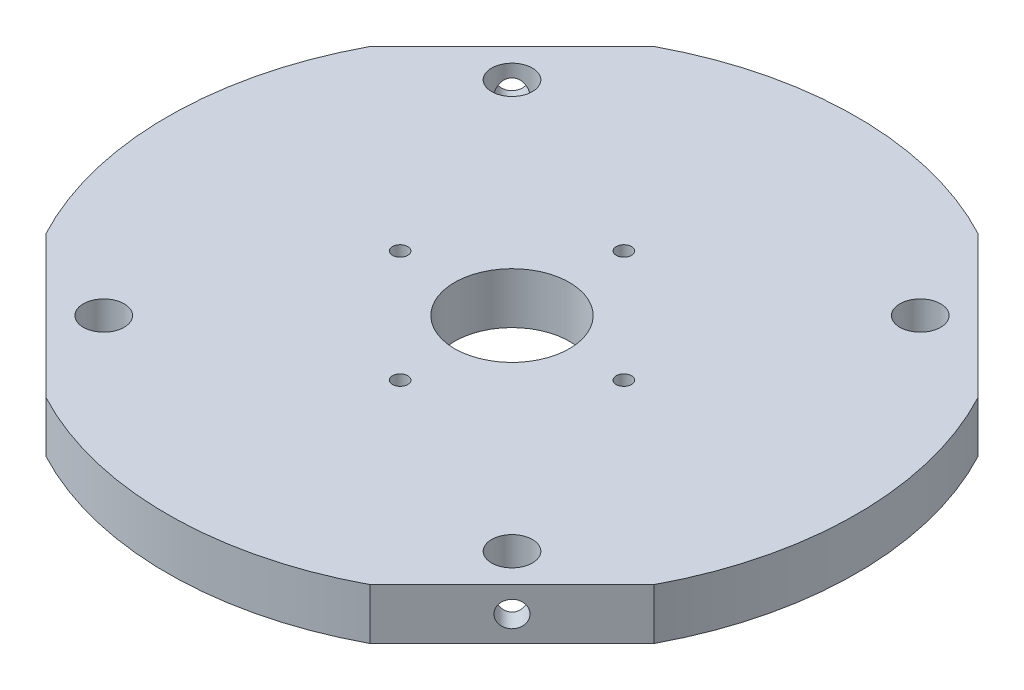
SolidWorks part; units mm, degrees
ref_plane "Front Plane" through (0, 0, 0) normal (0, 0, 1) x (1, 0, 0)
ref_plane "Top Plane" through (0, 0, 0) normal (0, 1, 0) x (1, 0, 0)
ref_plane "Right Plane" through (0, 0, 0) normal (1, 0, 0) x (0, 0, -1)
sketch "Sketch1" plane through (0, 0, 0) normal (0, 1, 0) x (1, 0, 0)
  circle A0 centre (0, 0) radius 67.5
  dimension "D1" = 135
extrude "Boss-Extrude1" add sketch "Sketch1" along normal blind 10
sketch "Sketch4" plane through (0, 10, 0) normal (0, 1, 0) x (1, 0, 0)
  line L0 (0, 67.5) -> (0, -67.5) construction
  line L1 (-67.5, 0) -> (67.5, 0) construction
  circle A0 centre (0, 0) radius 67.5 construction
  circle A1 centre (-40, 40) radius 4
  circle A2 centre (40, 40) radius 4
  circle A3 centre (40, -40) radius 4
  circle A4 centre (-40, -40) radius 4
  point P7 (0, 0)
  point P12 (0, 0)
  dimension "D3" = 8
  dimension "D1" = 40
  dimension "D2" = 40
extrude "Cut-Extrude1" cut sketch "Sketch4" against normal through all and the other way through all
sketch "Sketch5" plane through (0, 10, 0) normal (0, 1, 0) x (1, 0, 0)
  line L0 (-44.5962, 41.0607) -> (-41.0607, 44.5962) construction
  line L1 (-42.8284, 42.8284) -> (0, 0) construction
  line L2 (0, 67.5) -> (0, -67.5) construction
  line L3 (-31.7437, 59.57) -> (-59.57, 31.7437)
  line L4 (59.57, 31.7437) -> (31.7437, 59.57)
  line L5 (31.7437, -59.57) -> (59.57, -31.7437)
  line L6 (-59.57, -31.7437) -> (-31.7437, -59.57)
  line L7 (0, 0) -> (-45.6569, -45.6569) construction
  circle A0 centre (0, 0) radius 67.5 construction
  circle A1 centre (-40, 40) radius 4 construction
  point P5 (-42.8284, 42.8284)
  point P14 (0, 0)
  point P15 (-45.6569, 45.6569)
  dimension "D1" = 5
  dimension "D2" = 45
  dimension "D3" = 4
  dimension "D4" = 4
extrude "Cut-Extrude-Thin1" cut sketch "Sketch5" against normal through all thin
hole_wizard "Ø5.0mm Dowel Hole1" positions "Sketch6" profile "Sketch7" hole size "Ø5.0" standard "ANSI Metric"
sketch "Sketch6" plane through (45.6569, 0, 45.6569) normal (0.7071, 0, 0.7071) x (0.7071, 0, -0.7071)
  line L0 (0, 0) -> (0, 10) construction
  line L1 (-19.6762, 0) -> (19.6762, 0) construction
  line L2 (-19.6762, 10) -> (19.6762, 10) construction
  point P0 (0, 5)
sketch "Sketch7" plane through (45.6569, 5, 45.6569) normal (0, 1, 0) x (0.7071, 0, -0.7071)
  line L0 (0, 0) -> (0, 4)
  line L1 (0, 4) -> (2.5, 4)
  line L2 (2.5, 4) -> (2.5, 0)
  line L5 (2.5, 0) -> (0, 0)
  line L11 (0, -6.35) -> (0, 107.95) construction
  dimension "Thru Hole Dia." = 5
  dimension "Thru Hole Depth" = 4
pattern_circular "CirPattern1" count 4 over 360 about axis through (0, 10, 0) along (0, -1, 0) of "Ø5.0mm Dowel Hole1"
hole_wizard "Ø3.0mm Dowel Hole1" positions "Sketch8" profile "Sketch9" hole size "Ø3.0" standard "DIN" end condition through all
sketch "Sketch8" plane through (0, 0, 0) normal (0, -1, 0) x (-1, 0, 0)
  line L2 (67.5, 0) -> (-67.5, 0) construction
  line L3 (0, 67.5) -> (0, -67.5) construction
  line L4 (0, 0) -> (0, -19.661) construction
  line L6 (0, 0) -> (21.9203, 0)
  line L8 (0, 0) -> (0, -21.9203)
  arc A1 (59.57, -31.7437) -> (59.57, 31.7437) centre (0, 0) ccw construction
  arc A2 (-59.57, 31.7437) -> (-59.57, -31.7437) centre (0, 0) ccw construction
  arc A3 (31.7437, 59.57) -> (-31.7437, 59.57) centre (0, 0) ccw construction
  arc A4 (-31.7437, -59.57) -> (31.7437, -59.57) centre (0, 0) ccw construction
  point P68 (21.9203, 0)
  point P71 (-21.9203, 0)
  point P72 (0, -21.9203)
  point P75 (0, 21.9203)
  dimension "D1" = 31
sketch "Sketch9" plane through (0, 0, -21.9203) normal (1, 0, 0) x (0, 0, -1)
  line L0 (0, 0) -> (0, 10)
  line L1 (0, 10) -> (1.5, 10)
  line L2 (1.5, 10) -> (1.5, 0)
  line L5 (1.5, 0) -> (0, 0)
  line L11 (0, -6.35) -> (0, 107.95) construction
  dimension "Thru Hole Dia." = 3
  dimension "Thru Hole Depth" = 10
sketch "Sketch13" plane through (0, 10, 0) normal (0, 1, 0) x (1, 0, 0)
  circle A0 centre (0, 0) radius 11.25
  dimension "D1" = 22.5
extrude "Cut-Extrude2" cut sketch "Sketch13" against normal through all both and the other way through all
equation "\"Plate Thickness\"= 10mm"
equation "\"Plate Diameter\"= 135mm"
equation "\"D1@Sketch1\"=\"Plate Diameter\""
equation "\"D1@Boss-Extrude1\"=\"Plate Thickness\""
